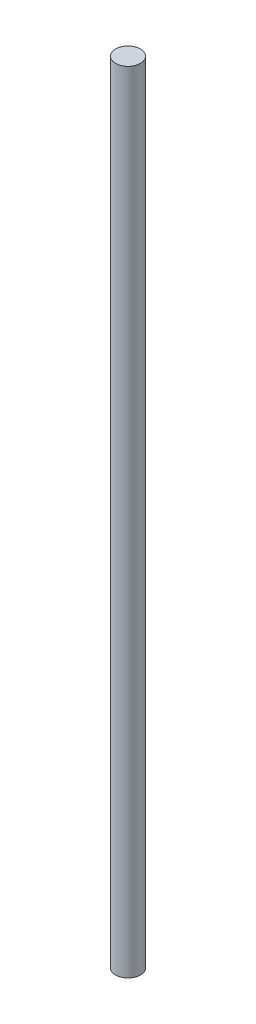
SolidWorks part; units mm, degrees
ref_plane "Front Plane" through (0, 0, 0) normal (0, 0, 1) x (1, 0, 0)
ref_plane "Top Plane" through (0, 0, 0) normal (0, 1, 0) x (1, 0, 0)
ref_plane "Right Plane" through (0, 0, 0) normal (1, 0, 0) x (0, 0, -1)
other "Configuration Table"
sketch "Sketch1" plane through (0, 0, 0) normal (0, 1, 0) x (1, 0, 0)
  circle A0 centre (550, 300) radius 6
extrude "OVEN_kesme_kilavuz_mili_D12_2" add sketch "Sketch1" along normal blind 380 from offset 400 separate body
